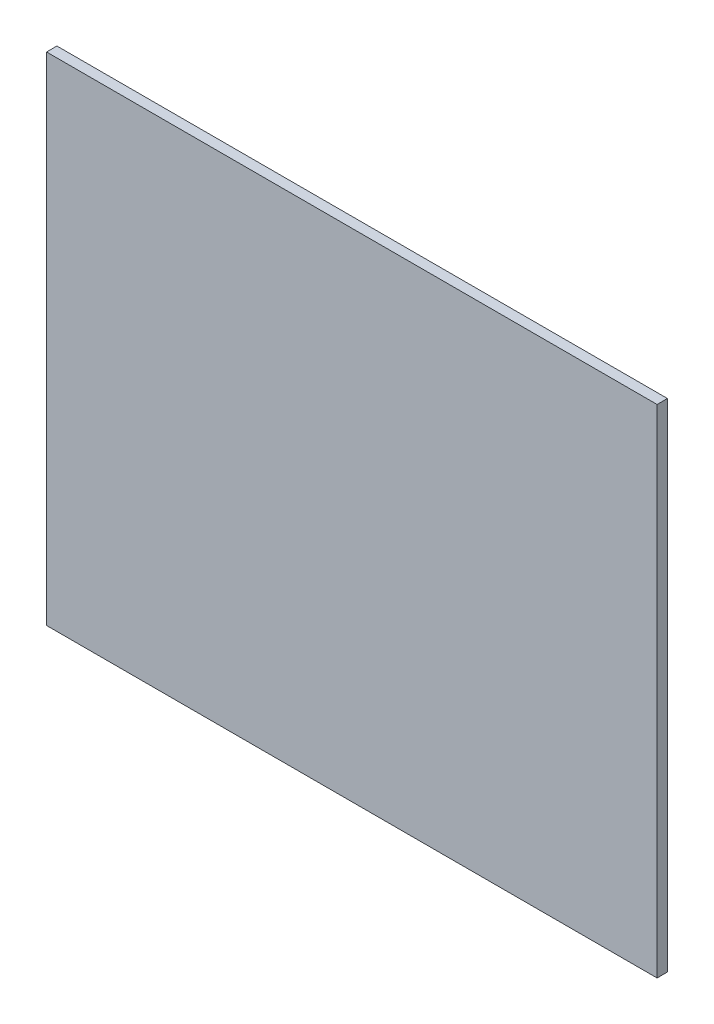
SolidWorks part; units mm, degrees
material "Pine"
ref_plane "Front Plane" through (0, 0, 0) normal (0, 0, 1) x (1, 0, 0)
ref_plane "Top Plane" through (0, 0, 0) normal (0, 1, 0) x (1, 0, 0)
ref_plane "Right Plane" through (0, 0, 0) normal (1, 0, 0) x (0, 0, -1)
sketch "Sketch2" plane through (0, 0, 0) normal (0, 0, 1) x (1, 0, 0)
  line L1 (-147.5, -120) -> (147.5, -120)
  line L2 (-147.5, -120) -> (-147.5, 120)
  line L3 (-147.5, 120) -> (147.5, 120)
  line L4 (147.5, -120) -> (147.5, 120)
  line L5 (-147.5, -120) -> (147.5, 120) construction
  line L6 (-147.5, 120) -> (147.5, -120) construction
  point P0 (0, 0)
  dimension "D1" = 295
  dimension "D2" = 240
extrude "Boss-Extrude1" add sketch "Sketch2" along normal blind 5
